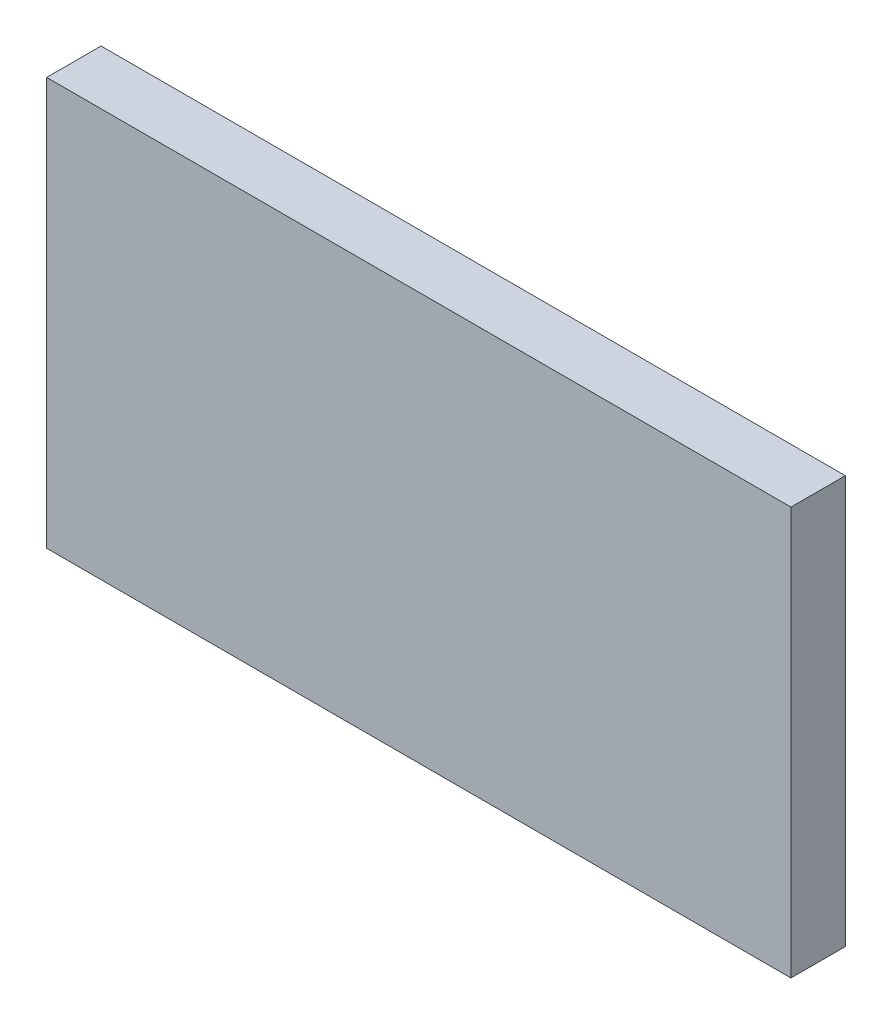
SolidWorks part; units mm, degrees
ref_plane "Front Plane" through (0, 0, 0) normal (0, 0, 1) x (1, 0, 0)
ref_plane "Top Plane" through (0, 0, 0) normal (0, 1, 0) x (1, 0, 0)
ref_plane "Right Plane" through (0, 0, 0) normal (1, 0, 0) x (0, 0, -1)
sketch "CurveSketch" plane through (0, 0, 0) normal (0, 0, 1) x (1, 0, 0)
  line L0 (-20.0525, -1.8635) -> (11.6665, -1.8635)
  line L1 (11.6665, -1.8635) -> (11.6665, 15.5175)
  line L2 (11.6665, 15.5175) -> (-20.0525, 15.5175)
  line L3 (-20.0525, 15.5175) -> (-20.0525, -1.8635)
extrude "CurveBoss" add sketch "CurveSketch" along normal blind 2.317
